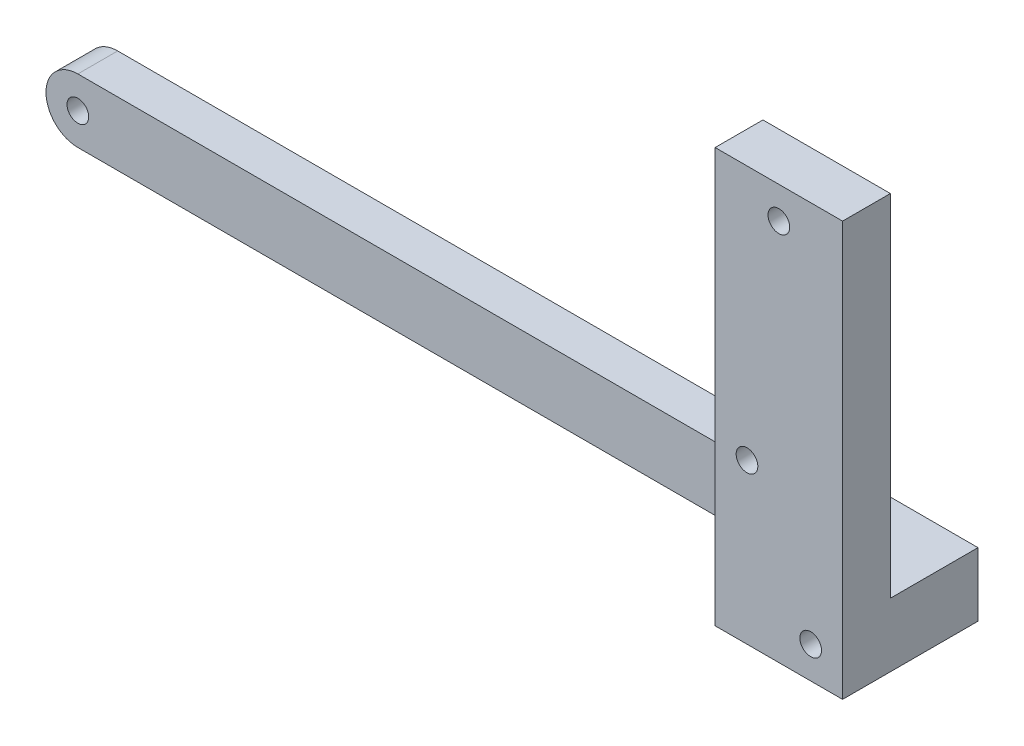
SolidWorks part; units mm, degrees
ref_plane "Front Plane" through (0, 0, 0) normal (0, 0, 1) x (1, 0, 0)
ref_plane "Top Plane" through (0, 0, 0) normal (0, 1, 0) x (1, 0, 0)
ref_plane "Right Plane" through (0, 0, 0) normal (1, 0, 0) x (0, 0, -1)
sketch "Sketch1" plane through (0, 0, 0) normal (0, 0, 1) x (1, 0, 0)
  line L3 (-12.7, 6.35) -> (12.7, 6.35)
  line L6 (-12.7, 6.35) -> (-12.7, -76.2)
  line L7 (-12.7, -76.2) -> (12.7, -76.2)
  line L8 (12.7, 6.35) -> (12.7, -76.2)
  circle A7 centre (0, 0) radius 2.159
  circle A8 centre (-6.35, -44.45) radius 2.159
  circle A9 centre (6.35, -69.85) radius 2.159
  dimension "D3" = 4.318
  dimension "D1" = 4.318
  dimension "D2" = 4.318
  dimension "D5" = 6.35
  dimension "D7" = 69.85
  dimension "D8" = 25.4
  dimension "D9" = 12.7
  dimension "D12" = 6.35
  dimension "D13" = 6.35
extrude "Boss-Extrude1" add sketch "Sketch1" along normal blind 9.525
ref_plane "Plane1" through (0, 0, -17.4625) normal (0, 0, 1) x (1, 0, 0)
sketch "Sketch5" plane through (0, 0, -17.4625) normal (0, 0, 1) x (1, 0, 0)
  line L1 (-158.75, -76.2) -> (12.7, -76.2)
  line L2 (12.7, -76.2) -> (12.7, -63.5)
  line L3 (12.7, -63.5) -> (-158.75, -63.5)
  arc A0 (-158.75, -63.5) -> (-158.75, -76.2) centre (-158.75, -69.85) ccw
  circle A1 centre (6.35, -69.85) radius 2.159 construction
  circle A2 centre (-158.75, -69.85) radius 2.159
  dimension "D3" = 12.7
  dimension "D4" = 4.318
  dimension "D1" = 165.1
  dimension "D2" = 69.85
extrude "Boss-Extrude2" add sketch "Sketch5" along normal blind 7.9375 separate body
sketch "Sketch6" plane through (0, 0, -17.4625) normal (0, 0, 1) x (1, 0, 0)
  line L1 (12.7, -63.5) -> (-12.7, -63.5)
  line L2 (12.7, -63.5) -> (12.7, -76.2)
  line L3 (12.7, -76.2) -> (-12.7, -76.2)
  line L4 (-12.7, -63.5) -> (-12.7, -76.2)
  circle A0 centre (6.35, -69.85) radius 2.159 construction
  circle A1 centre (6.35, -69.85) radius 2.159
extrude "Boss-Extrude3" add sketch "Sketch6" along normal up to surface (17.4625 mm away) up to face at (0, -34.925, 0)
